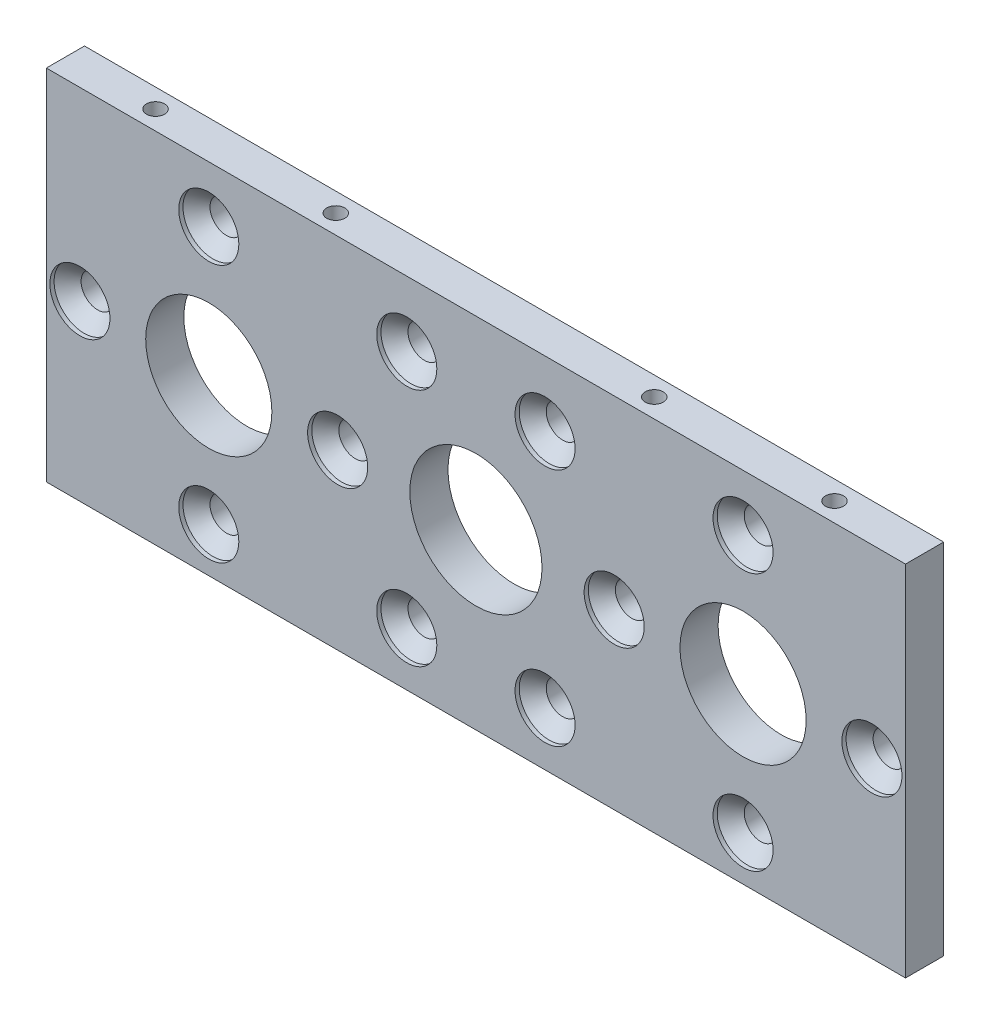
SolidWorks part; units mm, degrees
ref_plane "Plano frontal" through (0, 0, 0) normal (0, 0, 1) x (1, 0, 0)
ref_plane "Plano superior" through (0, 0, 0) normal (0, 1, 0) x (1, 0, 0)
ref_plane "Plano direito" through (0, 0, 0) normal (1, 0, 0) x (0, 0, -1)
sketch "Esboço1" plane through (0, 0, 0) normal (0, 0, 1) x (1, 0, 0)
  line L0 (71.505, 27.025) -> (-71.505, -27.025) construction
  line L1 (-71.505, 27.025) -> (71.505, 27.025)
  line L2 (-71.505, 27.025) -> (-71.505, -27.025)
  line L3 (-71.505, -27.025) -> (71.505, -27.025)
  line L4 (71.505, 27.025) -> (71.505, -27.025)
  dimension "D1" = 143.01
  dimension "D2" = 54.05
extrude "Ressalto-extrusão1" add sketch "Esboço1" along normal blind 6.35
sketch "Esboço2" plane through (0, 0, 0) normal (0, 0, -1) x (-1, 0, 0)
  circle A0 centre (-44.4631, 23.2919) radius 2.75
  circle A1 centre (-65.9131, 1.8419) radius 2.75
  circle A2 centre (-44.4631, -19.6081) radius 2.75
  circle A3 centre (-23.0131, 1.8419) radius 2.75
  circle A4 centre (-11.5056, 21.7734) radius 2.75
  circle A5 centre (11.5094, 21.7734) radius 2.75
  circle A6 centre (23.0169, 1.8419) radius 2.75
  circle A7 centre (11.5094, -18.0897) radius 2.75
  circle A8 centre (-11.5056, -18.0897) radius 2.75
  circle A9 centre (44.4669, -19.6081) radius 2.75
  circle A10 centre (65.9169, 1.8419) radius 2.75
  circle A11 centre (44.4669, 23.2919) radius 2.75
  dimension "D1" = 5.5
  dimension "D2" = 5.5
  dimension "D3" = 5.5
  dimension "D4" = 5.5
  dimension "D5" = 5.5
  dimension "D6" = 5.5
  dimension "D7" = 5.5
  dimension "D8" = 5.5
  dimension "D9" = 5.5
  dimension "D10" = 5.5
  dimension "D11" = 5.5
  dimension "D12" = 5.5
extrude "Corte-extrusão1" cut sketch "Esboço2" against normal blind 10
sketch "Esboço3" plane through (0, 0, 0) normal (0, 0, -1) x (-1, 0, 0)
  circle A0 centre (-44.4631, 1.8419) radius 10.5
  circle A1 centre (0.0019, 1.8419) radius 11
  circle A2 centre (44.4669, 1.8419) radius 10.5
  dimension "D1" = 22
  dimension "D2" = 21
  dimension "D3" = 21
extrude "Corte-extrusão2" cut sketch "Esboço3" against normal blind 10
sketch "Esboço4" plane through (0, 0, 0) normal (0, 0, 1) x (1, 0, 0)
  line L1 (-71.505, 27.025) -> (71.505, 27.025)
  line L2 (-71.505, 27.025) -> (-71.505, 30.645)
  line L3 (-71.505, 30.645) -> (71.505, 30.645)
  line L4 (71.505, 27.025) -> (71.505, 30.645)
  dimension "D1" = 143.01
  dimension "D2" = 3.62
extrude "Ressalto-extrusão2" add sketch "Esboço4" along normal blind 6.35
sketch "Croquis1" plane through (0, 0, 0) normal (0, 0, -1) x (-1, 0, 0)
  line L1 (-71.505, 30.645) -> (71.505, 30.645)
  line L2 (-71.505, 30.645) -> (-71.505, 32.645)
  line L3 (-71.505, 32.645) -> (71.505, 32.645)
  line L4 (71.505, 30.645) -> (71.505, 32.645)
  dimension "D1" = 2
extrude "Saliente-Extruir1" add sketch "Croquis1" against normal blind 6.35
sketch "Esboço8" plane through (0, 32.645, 0) normal (0, 1, 0) x (1, 0, 0)
  line L0 (71.505, -3.175) -> (-71.505, -3.175) construction
  line L3 (0, 0) -> (0, -6.35) construction
  circle A0 centre (56.505, -3.175) radius 1.5
  circle A1 centre (26.505, -3.175) radius 1.5
  circle A2 centre (-26.505, -3.175) radius 1.5
  circle A3 centre (-56.505, -3.175) radius 1.5
  dimension "D1" = 3
  dimension "D2" = 3
  dimension "D3" = 15
  dimension "D4" = 30
  dimension "D5" = 3.175
extrude "Corte-extrusão3" cut sketch "Esboço8" against normal blind 17
sketch "Esboço9" plane through (0, 0, 6.35) normal (0, 0, 1) x (1, 0, 0)
  circle A0 centre (44.4631, -19.6081) radius 5
  circle A1 centre (65.9131, 1.8419) radius 5
  circle A2 centre (44.4631, 23.2919) radius 5
  circle A3 centre (23.0131, 1.8419) radius 5
  circle A4 centre (11.5056, -18.0897) radius 5
  circle A5 centre (11.5056, 21.7734) radius 5
  circle A6 centre (-11.5094, 21.7734) radius 5
  circle A7 centre (-23.0169, 1.8419) radius 5
  circle A8 centre (-11.5094, -18.0897) radius 5
  circle A9 centre (-44.4669, 23.2919) radius 5
  circle A10 centre (-65.9169, 1.8419) radius 5
  circle A11 centre (-44.4669, -19.6081) radius 5
  dimension "D1" = 10
  dimension "D2" = 10
  dimension "D3" = 10
  dimension "D4" = 10
  dimension "D5" = 10
  dimension "D6" = 10
  dimension "D7" = 10
  dimension "D8" = 10
  dimension "D9" = 10
  dimension "D10" = 10
  dimension "D11" = 10
  dimension "D12" = 10
extrude "Corte-extrusão4" cut sketch "Esboço9" against normal blind 0.7
sketch "Esboço12" plane through (0, 0, 5.65) normal (0, 0, 1) x (1, 0, 0)
  circle A0 centre (-65.9169, 1.8419) radius 5
  circle A1 centre (-44.4669, 23.2919) radius 5
  circle A2 centre (-23.0169, 1.8419) radius 5
  circle A3 centre (-11.5094, 21.7734) radius 5
  circle A4 centre (-44.4669, -19.6081) radius 5
  circle A5 centre (-11.5094, -18.0897) radius 5
  circle A6 centre (11.5056, -18.0897) radius 5
  circle A7 centre (44.4631, -19.6081) radius 5
  circle A8 centre (23.0131, 1.8419) radius 5
  circle A9 centre (65.9131, 1.8419) radius 5
  circle A10 centre (44.4631, 23.2919) radius 5
  circle A11 centre (11.5056, 21.7734) radius 5
extrude "Corte-extrusão5" cut sketch "Esboço12" against normal blind 2.5 draft 45
